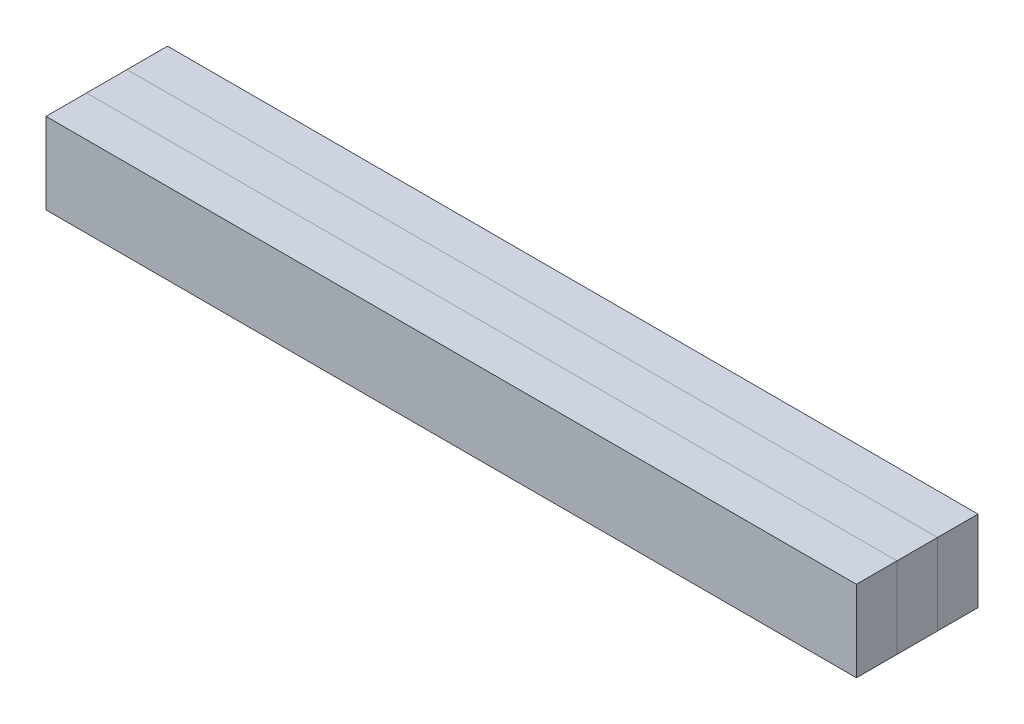
SolidWorks part; units mm, degrees
ref_plane "正面" through (0, 0, 0) normal (0, 0, 1) x (1, 0, 0)
ref_plane "平面" through (0, 0, 0) normal (0, 1, 0) x (1, 0, 0)
ref_plane "右側面" through (0, 0, 0) normal (1, 0, 0) x (0, 0, -1)
sketch "ｽｹｯﾁ1" plane through (0, 0, 0) normal (0, 0, 1) x (1, 0, 0)
  line L1 (0, 0) -> (100, 0)
  line L2 (0, 0) -> (0, 10)
  line L3 (0, 10) -> (100, 10)
  line L4 (100, 0) -> (100, 10)
extrude "ﾎﾞｽ - 押し出し1" add sketch "ｽｹｯﾁ1" along normal blind 5
sketch "ｽｹｯﾁ4" plane through (0, 0, 0) normal (0, 0, -1) x (-1, 0, 0)
  line L1 (0, 0) -> (-100, 0)
  line L2 (0, 0) -> (0, 10)
  line L3 (0, 10) -> (-100, 10)
  line L4 (-100, 0) -> (-100, 10)
extrude "ﾎﾞｽ - 押し出し3" add sketch "ｽｹｯﾁ4" along normal blind 5 separate body
sketch "ｽｹｯﾁ5" plane through (0, 0, -5) normal (0, 0, -1) x (-1, 0, 0)
  line L0 (0, 10) -> (-100, 10) construction
  line L1 (0, 0) -> (-100, 0)
  line L2 (0, 0) -> (0, 10)
  line L3 (0, 10) -> (-100, 10)
  line L4 (-100, 0) -> (-100, 10)
extrude "ﾎﾞｽ - 押し出し4" add sketch "ｽｹｯﾁ5" along normal blind 5 separate body
